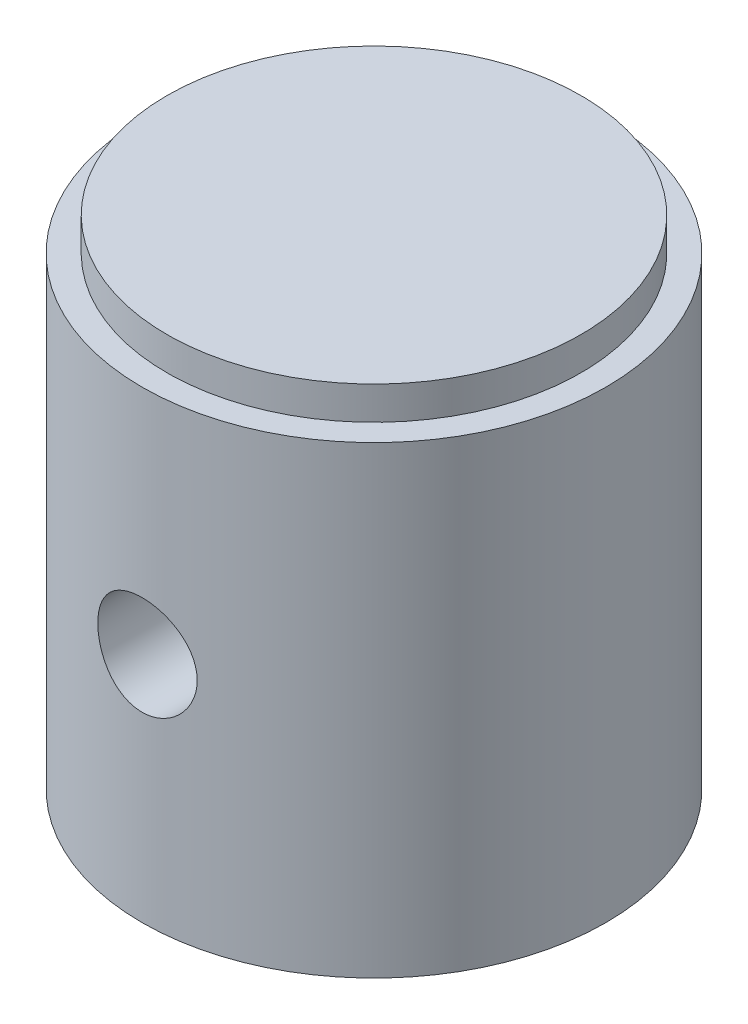
SolidWorks part; units mm, degrees
ref_plane "Front Plane" through (0, 0, 0) normal (0, 0, 1) x (1, 0, 0)
ref_plane "Top Plane" through (0, 0, 0) normal (0, 1, 0) x (1, 0, 0)
ref_plane "Right Plane" through (0, 0, 0) normal (1, 0, 0) x (0, 0, -1)
sketch "Sketch1" plane through (0, 0, 0) normal (0, 0, 1) x (1, 0, 0)
  line L0 (0, 1.1459) -> (0, -3.3891) construction
  line L1 (0, 1.1459) -> (-6.25, 1.1459)
  line L2 (-6.25, 1.1459) -> (-6.25, 0.1459)
  line L3 (-6.25, 0.1459) -> (-7, 0.1459)
  line L4 (-7, 0.1459) -> (-7, -13.8541)
  line L5 (-7, -13.8541) -> (-6.25, -13.8541)
  line L6 (-6.25, -13.8541) -> (-4.75, -9.7329)
  line L7 (-4.75, -9.7329) -> (-4.75, -2.8541)
  line L8 (-4.75, -2.8541) -> (0, 0)
  line L9 (0, 0) -> (0, 1.1459)
  dimension "D1" = 7
  dimension "D2" = 15
  dimension "D3" = 1
  dimension "D4" = 6.25
  dimension "D5" = 4.75
  dimension "D6" = 20
  dimension "D7" = 59
  dimension "D8" = 6.25
  dimension "D9" = 11
revolve "Revolve1" add sketch "Sketch1" angle 360 about L0
sketch "Sketch2" plane through (0, 0, 0) normal (0, 0, 1) x (1, 0, 0)
  line L0 (-7, -13.8541) -> (7, -13.8541) construction
  circle A0 centre (0, -6.8541) radius 1.5
  point P5 (0, 0)
  dimension "D1" = 3
  dimension "D2" = 7
extrude "Cut-Extrude1" cut sketch "Sketch2" against normal through all both and the other way through all
